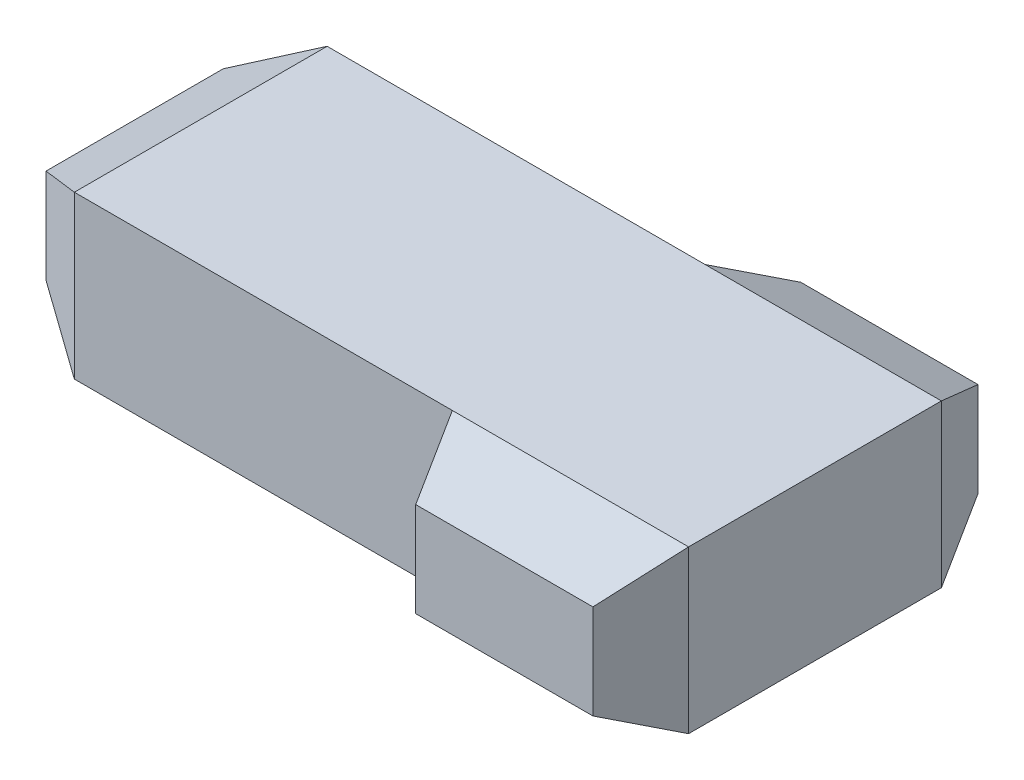
SolidWorks part; units mm, degrees
ref_plane "Front Plane" through (0, 0, 0) normal (0, 0, 1) x (1, 0, 0)
ref_plane "Top Plane" through (0, 0, 0) normal (0, 1, 0) x (1, 0, 0)
ref_plane "Right Plane" through (0, 0, 0) normal (1, 0, 0) x (0, 0, -1)
sketch "Sketch1" plane through (0, 0, 0) normal (0, 1, 0) x (1, 0, 0)
  line L1 (13, -5.35) -> (-13, -5.35)
  line L2 (13, -5.35) -> (13, 5.35)
  line L3 (13, 5.35) -> (-13, 5.35)
  line L4 (-13, -5.35) -> (-13, 5.35)
  line L5 (13, -5.35) -> (-13, 5.35) construction
  line L6 (13, 5.35) -> (-13, -5.35) construction
  point P0 (0, 0)
  dimension "D1" = 26
  dimension "D2" = 10.7
extrude "Boss-Extrude1" add sketch "Sketch1" along normal blind 6.85
ref_plane "Plane1" through (-15.8, 0, 0) normal (-1, 0, 0) x (0, 0, 1)
sketch "Sketch2" plane through (-15.8, 0, 0) normal (-1, 0, 0) x (0, 0, 1)
  line L0 (0, -3.7675) -> (0, 3.7675) construction
  line L1 (3.75, 1.425) -> (-3.75, 1.425)
  line L2 (3.75, 1.425) -> (3.75, 5.425)
  line L3 (3.75, 5.425) -> (-3.75, 5.425)
  line L4 (-3.75, 1.425) -> (-3.75, 5.425)
  line L5 (3.75, 1.425) -> (-3.75, 5.425) construction
  line L6 (3.75, 5.425) -> (-3.75, 1.425) construction
  line L7 (5.885, 0) -> (-5.885, 0) construction
  point P0 (0, 3.425)
  dimension "D1" = 7.5
  dimension "D2" = 4
  dimension "D3" = 3.425
loft "Loft1" add profiles "Sketch2" section "Sketch2" section face at (-13, 3.425, 0)
ref_plane "Plane2" through (0, 0, 8.15) normal (0, 0, 1) x (1, 0, 0)
sketch "Sketch3" plane through (0, 0, 8.15) normal (0, 0, 1) x (1, 0, 0)
  line L0 (5.885, 0) -> (-5.885, 0) construction
  line L1 (4.25, 1.425) -> (11.75, 1.425)
  line L2 (4.25, 1.425) -> (4.25, 5.425)
  line L3 (4.25, 5.425) -> (11.75, 5.425)
  line L4 (11.75, 1.425) -> (11.75, 5.425)
  line L5 (4.25, 1.425) -> (11.75, 5.425) construction
  line L6 (4.25, 5.425) -> (11.75, 1.425) construction
  line L7 (13, 6.85) -> (13, 0) construction
  point P0 (8, 3.425)
  dimension "D1" = 7.5
  dimension "D2" = 4
  dimension "D3" = 3.425
  dimension "D4" = 5
sketch "Sketch4" plane through (0, 0, 5.35) normal (0, 0, 1) x (1, 0, 0)
  line L0 (7.425, 0) -> (-7.425, 0) construction
  line L1 (13, 6.85) -> (3, 6.85)
  line L2 (13, 6.85) -> (13, 0)
  line L3 (13, 0) -> (3, 0)
  line L4 (3, 6.85) -> (3, 0)
  line L6 (4.25, 1.425) -> (4.25, 5.425) construction
  dimension "D1" = 1.25
loft "Loft2" add profiles "Sketch4", "Sketch3"
mirror "Mirror1" about plane through (0, 0, 0) normal (0, 0, 1) of "Loft2"
